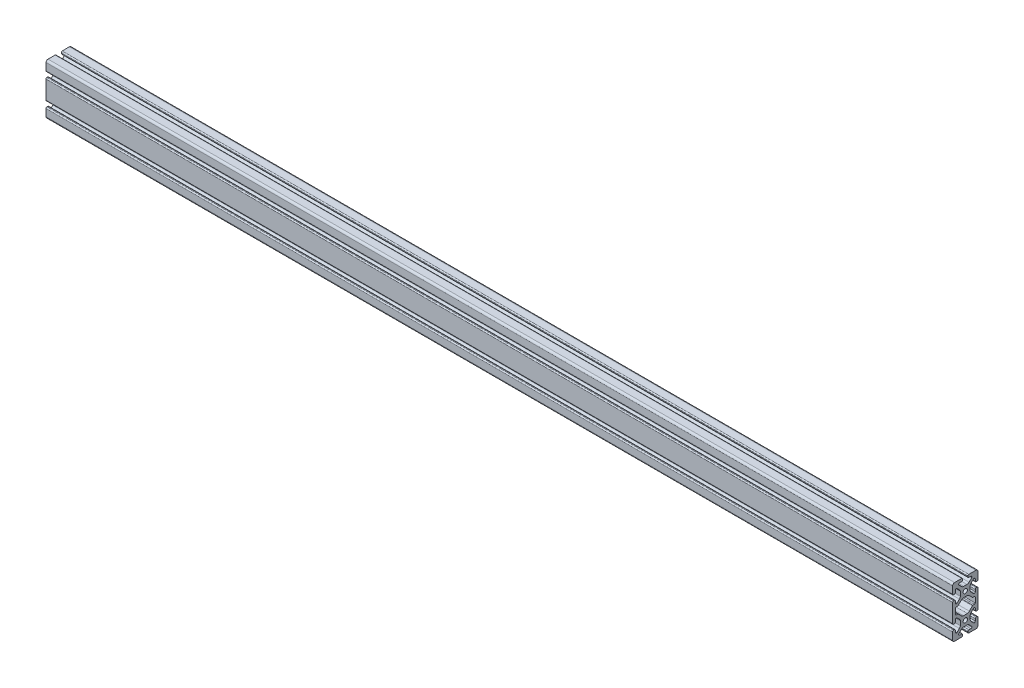
SolidWorks part; units mm, degrees
ref_plane "Front Plane" through (0, 0, 0) normal (0, 0, 1) x (1, 0, 0)
ref_plane "Top Plane" through (0, 0, 0) normal (0, 1, 0) x (1, 0, 0)
ref_plane "Right Plane" through (0, 0, 0) normal (1, 0, 0) x (0, 0, -1)
ref_plane "Plane1" through (-1427, 0, 0) normal (-1, 0, 0) x (0, -1, 0)
sketch "Sketch1" plane through (-1427, 0, 0) normal (-1, 0, 0) x (0, -1, 0)
  line L0 (-41.0621, 210.433) -> (-41.0621, 212.7134)
  line L1 (-41.4341, 213.6115) -> (-46.3191, 218.4965)
  line L2 (-48.0045, 221.5839) -> (-48.0045, 227.568)
  line L3 (-46.9215, 230.5872) -> (-41.4341, 236.0746)
  line L4 (-41.0621, 236.9727) -> (-41.0621, 239.2531)
  line L5 (-39.7921, 240.5231) -> (-31.6486, 240.5231)
  line L6 (-30.3786, 239.2531) -> (-30.3786, 236.9727)
  line L7 (-30.0066, 236.0746) -> (-24.5192, 230.5872)
  line L8 (-23.4362, 227.568) -> (-23.4362, 221.5839)
  line L9 (-25.1216, 218.4965) -> (-30.0066, 213.6115)
  line L10 (-30.3786, 212.7134) -> (-30.3786, 210.433)
  line L11 (-31.6486, 209.163) -> (-39.7921, 209.163)
  line L12 (-0.0405, 219.2159) -> (-0.0405, 216.131)
  line L13 (-1.6105, 214.5611) -> (-2.0689, 214.5611)
  line L14 (-2.6063, 214.7837) -> (-6.7091, 218.8864)
  line L15 (-8.0045, 222.2721) -> (-8.0045, 227.345)
  line L16 (-6.8049, 230.7038) -> (-2.5485, 234.9602)
  line L17 (-2.0111, 235.1828) -> (-1.6094, 235.1828)
  line L18 (-0.0405, 233.5549) -> (-0.0405, 230.47)
  line L19 (1.5294, 228.9001) -> (2.7103, 228.9001)
  line L20 (4.2794, 230.4187) -> (4.2794, 241.6747)
  line L21 (1.3349, 244.8439) -> (-9.9211, 244.8439)
  line L22 (-11.6602, 243.2831) -> (-11.6602, 242.093)
  line L23 (-10.0902, 240.5231) -> (-7.0054, 240.5231)
  line L24 (-5.4354, 238.9531) -> (-5.4354, 238.4975)
  line L25 (-5.658, 237.9601) -> (-9.4108, 234.2072)
  line L26 (-12.3788, 232.543) -> (-19.0619, 232.543)
  line L27 (-22.0299, 234.2072) -> (-25.7827, 237.9601)
  line L28 (-26.0053, 238.4975) -> (-26.0053, 238.9531)
  line L29 (-24.4354, 240.5231) -> (-21.3505, 240.5231)
  line L30 (-19.7805, 242.093) -> (-19.7805, 243.274)
  line L31 (-21.3505, 244.8439) -> (-50.0902, 244.8439)
  line L32 (-51.6601, 243.274) -> (-51.6601, 242.093)
  line L33 (-50.0902, 240.5231) -> (-47.0053, 240.5231)
  line L34 (-45.4354, 238.9531) -> (-45.4354, 238.4975)
  line L35 (-45.658, 237.9601) -> (-49.4108, 234.2072)
  line L36 (-52.3788, 232.543) -> (-59.0618, 232.543)
  line L37 (-62.0298, 234.2072) -> (-65.7826, 237.9601)
  line L38 (-66.0052, 238.4975) -> (-66.0052, 238.9531)
  line L39 (-64.4353, 240.5231) -> (-61.3504, 240.5231)
  line L40 (-59.7805, 242.093) -> (-59.7805, 243.2831)
  line L41 (-61.5196, 244.8439) -> (-72.7756, 244.8439)
  line L42 (-75.7201, 241.6747) -> (-75.7201, 230.4187)
  line L43 (-74.151, 228.9001) -> (-72.9701, 228.9001)
  line L44 (-71.4001, 230.47) -> (-71.4001, 233.5549)
  line L45 (-69.8312, 235.1828) -> (-69.4296, 235.1828)
  line L46 (-68.8922, 234.9602) -> (-64.6358, 230.7038)
  line L47 (-63.4362, 227.345) -> (-63.4362, 222.2721)
  line L48 (-64.7316, 218.8864) -> (-68.8343, 214.7837)
  line L49 (-69.3718, 214.5611) -> (-69.8302, 214.5611)
  line L50 (-71.4001, 216.131) -> (-71.4001, 219.2159)
  line L51 (-72.8657, 220.7824) -> (-74.0466, 220.7824)
  line L52 (-75.7201, 219.2672) -> (-75.7201, 208.0039)
  line L53 (-72.5508, 204.8425) -> (-61.2901, 204.8425)
  line L54 (-59.7805, 206.4113) -> (-59.7805, 207.593)
  line L55 (-61.3504, 209.163) -> (-64.4353, 209.163)
  line L56 (-66.0052, 210.7329) -> (-66.0052, 211.1886)
  line L57 (-65.7826, 211.726) -> (-61.6284, 215.8802)
  line L58 (-58.2697, 217.143) -> (-53.1709, 217.143)
  line L59 (-49.8122, 215.8802) -> (-45.658, 211.726)
  line L60 (-45.4354, 211.1886) -> (-45.4354, 210.7329)
  line L61 (-47.0053, 209.163) -> (-50.0902, 209.163)
  line L62 (-51.6601, 207.5931) -> (-51.6601, 206.4122)
  line L63 (-50.0902, 204.8425) -> (-21.3505, 204.8425)
  line L64 (-19.7805, 206.4122) -> (-19.7805, 207.5931)
  line L65 (-21.3505, 209.163) -> (-24.4354, 209.163)
  line L66 (-26.0053, 210.7329) -> (-26.0053, 211.1886)
  line L67 (-25.7827, 211.726) -> (-21.6285, 215.8802)
  line L68 (-18.2697, 217.143) -> (-13.171, 217.143)
  line L69 (-9.8122, 215.8802) -> (-5.658, 211.726)
  line L70 (-5.4354, 211.1886) -> (-5.4354, 210.7329)
  line L71 (-7.0054, 209.163) -> (-10.0902, 209.163)
  line L72 (-11.6602, 207.593) -> (-11.6602, 206.4113)
  line L73 (-10.1506, 204.8425) -> (1.1102, 204.8425)
  line L74 (4.2794, 208.0039) -> (4.2794, 219.2672)
  line L75 (2.606, 220.7824) -> (1.4251, 220.7824)
  arc A0 (-39.7921, 209.163) -> (-41.0621, 210.433) centre (-39.7921, 210.433) cw
  arc A1 (-41.0621, 212.7134) -> (-41.4341, 213.6115) centre (-42.3321, 212.7134) ccw
  arc A2 (-46.3191, 218.4965) -> (-48.0045, 221.5839) centre (-43.2888, 222.1544) cw
  arc A3 (-48.0045, 227.568) -> (-46.9215, 230.5872) centre (-43.2545, 227.568) cw
  arc A4 (-41.4341, 236.0746) -> (-41.0621, 236.9727) centre (-42.3321, 236.9727) ccw
  arc A5 (-41.0621, 239.2531) -> (-39.7921, 240.5231) centre (-39.7921, 239.2531) cw
  arc A6 (-31.6486, 240.5231) -> (-30.3786, 239.2531) centre (-31.6486, 239.2531) cw
  arc A7 (-30.3786, 236.9727) -> (-30.0066, 236.0746) centre (-29.1086, 236.9727) ccw
  arc A8 (-24.5192, 230.5872) -> (-23.4362, 227.568) centre (-28.1862, 227.568) cw
  arc A9 (-23.4362, 221.5839) -> (-25.1216, 218.4965) centre (-28.1518, 222.1544) cw
  arc A10 (-30.0066, 213.6115) -> (-30.3786, 212.7134) centre (-29.1086, 212.7134) ccw
  arc A11 (-30.3786, 210.433) -> (-31.6486, 209.163) centre (-31.6486, 210.433) cw
  circle A12 centre (-55.7203, 224.843) radius 3.4
  circle A13 centre (-15.7203, 224.843) radius 3.4
  arc A14 (-0.0405, 216.131) -> (-1.6105, 214.5611) centre (-1.6105, 216.131) cw
  arc A15 (-2.0689, 214.5611) -> (-2.6063, 214.7837) centre (-2.0689, 215.3211) cw
  arc A16 (-6.7091, 218.8864) -> (-8.0045, 222.2721) centre (-3.2561, 222.1482) cw
  arc A17 (-8.0045, 227.345) -> (-6.8049, 230.7038) centre (-3.2586, 227.5437) cw
  arc A18 (-2.5485, 234.9602) -> (-2.0111, 235.1828) centre (-2.0111, 234.4228) cw
  arc A19 (-1.6094, 235.1828) -> (-0.0405, 233.5549) centre (-1.6094, 233.6129) cw
  arc A20 (-0.0405, 230.47) -> (1.5294, 228.9001) centre (1.5294, 230.47) ccw
  arc A21 (2.7103, 228.9001) -> (4.2794, 230.4187) centre (2.7103, 230.47) ccw
  arc A22 (4.2794, 241.6747) -> (1.3349, 244.8439) centre (1.1102, 241.6826) ccw
  arc A23 (-9.9211, 244.8439) -> (-11.6602, 243.2831) centre (-10.0902, 243.2831) ccw
  arc A24 (-11.6602, 242.093) -> (-10.0902, 240.5231) centre (-10.0902, 242.093) ccw
  arc A25 (-7.0054, 240.5231) -> (-5.4354, 238.9531) centre (-7.0054, 238.9531) cw
  arc A26 (-5.4354, 238.4975) -> (-5.658, 237.9601) centre (-6.1954, 238.4975) cw
  arc A27 (-9.4108, 234.2072) -> (-12.3788, 232.543) centre (-13.0638, 237.2434) cw
  arc A28 (-19.0619, 232.543) -> (-22.0299, 234.2072) centre (-18.3769, 237.2434) cw
  arc A29 (-25.7827, 237.9601) -> (-26.0053, 238.4975) centre (-25.2453, 238.4975) cw
  arc A30 (-26.0053, 238.9531) -> (-24.4354, 240.5231) centre (-24.4354, 238.9531) cw
  arc A31 (-21.3505, 240.5231) -> (-19.7805, 242.093) centre (-21.3505, 242.093) ccw
  arc A32 (-19.7805, 243.274) -> (-21.3505, 244.8439) centre (-21.3505, 243.274) ccw
  arc A33 (-50.0902, 244.8439) -> (-51.6601, 243.274) centre (-50.0902, 243.274) ccw
  arc A34 (-51.6601, 242.093) -> (-50.0902, 240.5231) centre (-50.0902, 242.093) ccw
  arc A35 (-47.0053, 240.5231) -> (-45.4354, 238.9531) centre (-47.0053, 238.9531) cw
  arc A36 (-45.4354, 238.4975) -> (-45.658, 237.9601) centre (-46.1954, 238.4975) cw
  arc A37 (-49.4108, 234.2072) -> (-52.3788, 232.543) centre (-53.0638, 237.2434) cw
  arc A38 (-59.0618, 232.543) -> (-62.0298, 234.2072) centre (-58.3768, 237.2434) cw
  arc A39 (-65.7826, 237.9601) -> (-66.0052, 238.4975) centre (-65.2452, 238.4975) cw
  arc A40 (-66.0052, 238.9531) -> (-64.4353, 240.5231) centre (-64.4353, 238.9531) cw
  arc A41 (-61.3504, 240.5231) -> (-59.7805, 242.093) centre (-61.3504, 242.093) ccw
  arc A42 (-59.7805, 243.2831) -> (-61.5196, 244.8439) centre (-61.3504, 243.2831) ccw
  arc A43 (-72.7756, 244.8439) -> (-75.7201, 241.6747) centre (-72.5508, 241.6826) ccw
  arc A44 (-75.7201, 230.4187) -> (-74.151, 228.9001) centre (-74.151, 230.47) ccw
  arc A45 (-72.9701, 228.9001) -> (-71.4001, 230.47) centre (-72.9701, 230.47) ccw
  arc A46 (-71.4001, 233.5549) -> (-69.8312, 235.1828) centre (-69.8312, 233.6129) cw
  arc A47 (-69.4296, 235.1828) -> (-68.8922, 234.9602) centre (-69.4296, 234.4228) cw
  arc A48 (-64.6358, 230.7038) -> (-63.4362, 227.345) centre (-68.182, 227.5437) cw
  arc A49 (-63.4362, 222.2721) -> (-64.7316, 218.8864) centre (-68.1846, 222.1482) cw
  arc A50 (-68.8343, 214.7837) -> (-69.3718, 214.5611) centre (-69.3718, 215.3211) cw
  arc A51 (-69.8302, 214.5611) -> (-71.4001, 216.131) centre (-69.8302, 216.131) cw
  arc A52 (-71.4001, 219.2159) -> (-72.8657, 220.7824) centre (-72.9701, 219.2159) ccw
  arc A53 (-74.0466, 220.7824) -> (-75.7201, 219.2672) centre (-74.151, 219.2159) ccw
  arc A54 (-75.7201, 208.0039) -> (-72.5508, 204.8425) centre (-72.5508, 208.0118) ccw
  arc A55 (-61.2901, 204.8425) -> (-59.7805, 206.4113) centre (-61.3504, 206.4113) ccw
  arc A56 (-59.7805, 207.593) -> (-61.3504, 209.163) centre (-61.3504, 207.593) ccw
  arc A57 (-64.4353, 209.163) -> (-66.0052, 210.7329) centre (-64.4353, 210.7329) cw
  arc A58 (-66.0052, 211.1886) -> (-65.7826, 211.726) centre (-65.2452, 211.1886) cw
  arc A59 (-61.6284, 215.8802) -> (-58.2697, 217.143) centre (-58.4013, 212.3949) cw
  arc A60 (-53.1709, 217.143) -> (-49.8122, 215.8802) centre (-53.0393, 212.3949) cw
  arc A61 (-45.658, 211.726) -> (-45.4354, 211.1886) centre (-46.1954, 211.1886) cw
  arc A62 (-45.4354, 210.7329) -> (-47.0053, 209.163) centre (-47.0053, 210.7329) cw
  arc A63 (-50.0902, 209.163) -> (-51.6601, 207.5931) centre (-50.0902, 207.593) ccw
  arc A64 (-51.6601, 206.4122) -> (-50.0902, 204.8425) centre (-50.0902, 206.4125) ccw
  arc A65 (-21.3505, 204.8425) -> (-19.7805, 206.4122) centre (-21.3505, 206.4125) ccw
  arc A66 (-19.7805, 207.5931) -> (-21.3505, 209.163) centre (-21.3505, 207.593) ccw
  arc A67 (-24.4354, 209.163) -> (-26.0053, 210.7329) centre (-24.4354, 210.7329) cw
  arc A68 (-26.0053, 211.1886) -> (-25.7827, 211.726) centre (-25.2453, 211.1886) cw
  arc A69 (-21.6285, 215.8802) -> (-18.2697, 217.143) centre (-18.4013, 212.3949) cw
  arc A70 (-13.171, 217.143) -> (-9.8122, 215.8802) centre (-13.0394, 212.3949) cw
  arc A71 (-5.658, 211.726) -> (-5.4354, 211.1886) centre (-6.1954, 211.1886) cw
  arc A72 (-5.4354, 210.7329) -> (-7.0054, 209.163) centre (-7.0054, 210.7329) cw
  arc A73 (-10.0902, 209.163) -> (-11.6602, 207.593) centre (-10.0902, 207.593) ccw
  arc A74 (-11.6602, 206.4113) -> (-10.1506, 204.8425) centre (-10.0902, 206.4113) ccw
  arc A75 (1.1102, 204.8425) -> (4.2794, 208.0039) centre (1.1102, 208.0118) ccw
  arc A76 (4.2794, 219.2672) -> (2.606, 220.7824) centre (2.7103, 219.2159) ccw
  arc A77 (1.4251, 220.7824) -> (-0.0405, 219.2159) centre (1.5294, 219.2159) ccw
  dimension "D1" = 6.8
  dimension "D2" = 1.27
  dimension "D3" = 1.57
  dimension "D4" = 0.76
  dimension "D5" = 3.1693
  dimension "D6" = 15.7203
  dimension "D7" = 55.7203
  dimension "D8" = 224.843
extrude "Boss-Extrude1" add sketch "Sketch1" against normal blind 1427
